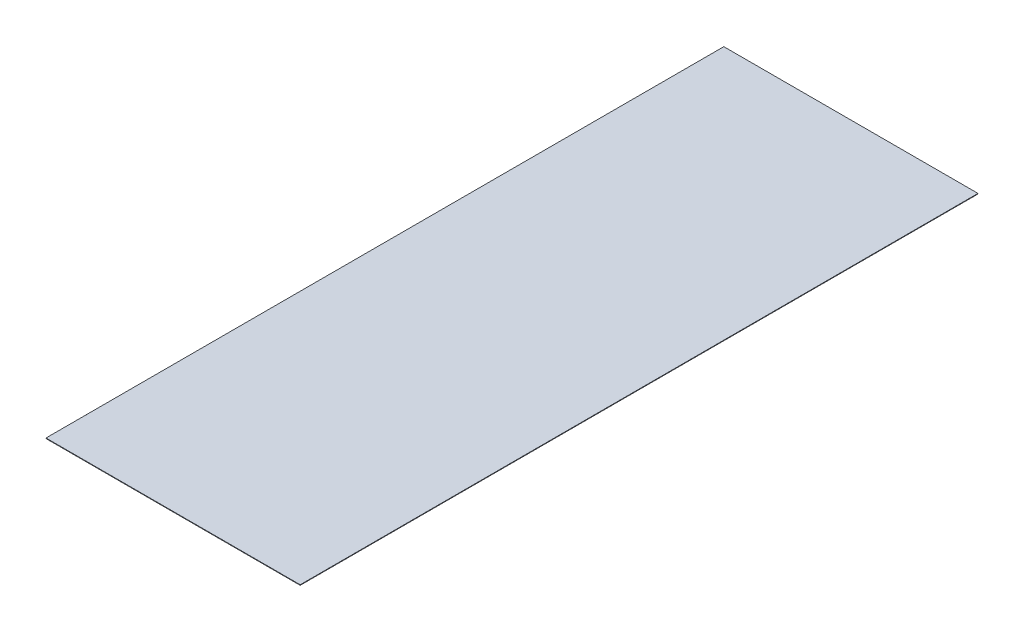
SolidWorks part; units mm, degrees
material "ASTM A36 Acero"
ref_plane "Alzado" through (0, 0, 0) normal (0, 0, 1) x (1, 0, 0)
ref_plane "Planta" through (0, 0, 0) normal (0, 1, 0) x (1, 0, 0)
ref_plane "Vista lateral" through (0, 0, 0) normal (1, 0, 0) x (0, 0, -1)
sketch "Croquis1" plane through (0, 0, 0) normal (0, 1, 0) x (1, 0, 0)
  line L1 (-457.2, -1219.2) -> (457.2, -1219.2)
  line L2 (-457.2, -1219.2) -> (-457.2, 1219.2)
  line L3 (-457.2, 1219.2) -> (457.2, 1219.2)
  line L4 (457.2, -1219.2) -> (457.2, 1219.2)
  line L5 (-457.2, -1219.2) -> (457.2, 1219.2) construction
  line L6 (-457.2, 1219.2) -> (457.2, -1219.2) construction
  point P0 (0, 0)
  dimension "D1" = 2438.4
  dimension "D2" = 914.4
extrude "Saliente-Extruir1" add sketch "Croquis1" along normal blind 1.9
